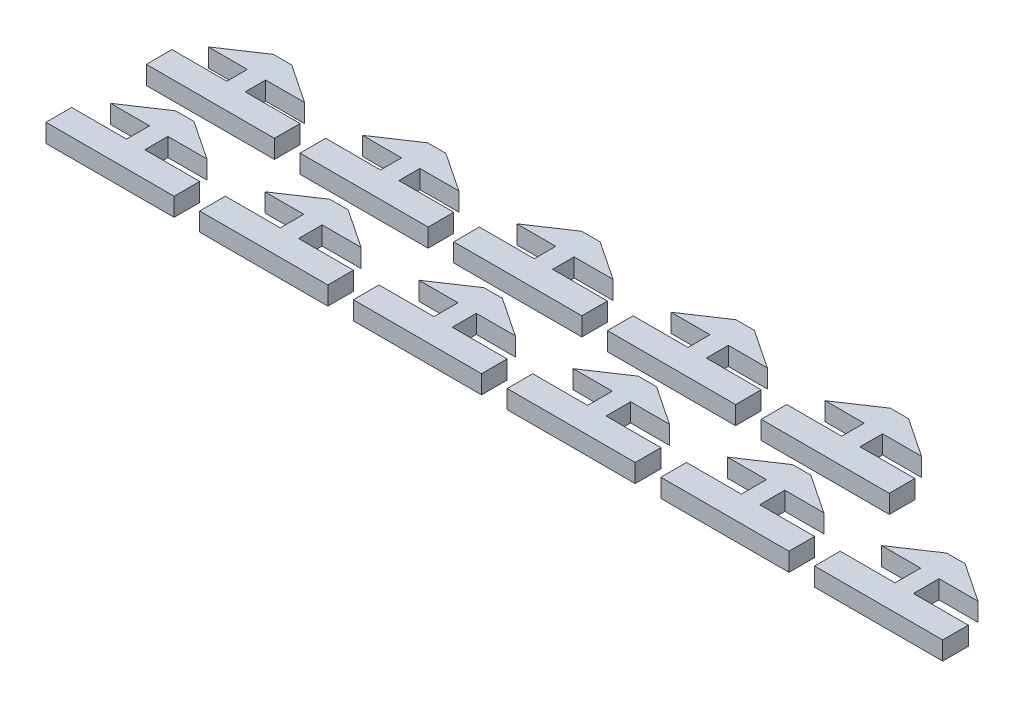
SolidWorks part; units mm, degrees
ref_plane "Front" through (0, 0, 0) normal (0, 0, 1) x (1, 0, 0)
ref_plane "Top" through (0, 0, 0) normal (0, 1, 0) x (1, 0, 0)
ref_plane "Right" through (0, 0, 0) normal (1, 0, 0) x (0, 0, -1)
sketch "Sketch1" plane through (0, 0, 0) normal (0, 1, 0) x (1, 0, 0)
  line L0 (-1.7907, 2) -> (-9.398, 2)
  line L2 (-1.7907, -2) -> (-1.7907, 2)
  line L4 (1.7907, -2) -> (1.7907, 2)
  line L7 (-9.398, 2) -> (-1.7907, 7.08)
  line L8 (-1.7907, 7.08) -> (1.7907, 7.08)
  line L9 (1.7907, 7.08) -> (9.398, 2)
  line L10 (9.398, 2) -> (1.7907, 2)
  line L11 (1.7907, -2) -> (12.5, -2)
  line L12 (-1.7907, -2) -> (-12.5, -2)
  line L13 (-12.5, -2) -> (-12.5, -7)
  line L14 (-12.5, -7) -> (12.5, -7)
  line L15 (12.5, -7) -> (12.5, -2)
  line L16 (12.5, -2) -> (1.7907, -2)
  point P0 (0, 0)
  point P6 (0, -7)
  point P17 (0, 7.08)
  point P24 (1.7907, 0)
  dimension "D1" = 18.796
  dimension "D2" = 3.5814
  dimension "D3" = 25
  dimension "D4" = 5
  dimension "D5" = 5.08
  dimension "D7" = 4
extrude "Boss-Extrude1" add sketch "Sketch1" along normal blind 3.5814 contours L14 L15 L11 L4 L10 L9 L8 L7 L0 L2 L12 L13
sketch "Sketch2" plane through (0, 0, 0) normal (0, 1, 0) x (1, 0, 0)
  line L0 (28.2093, 2.1) -> (20.602, 2.1)
  line L1 (28.2093, -2) -> (28.2093, 2.1)
  line L2 (31.7907, -2) -> (31.7907, 2.1)
  line L3 (20.602, 2.1) -> (28.2093, 7.18)
  line L4 (28.2093, 7.18) -> (31.7907, 7.18)
  line L5 (31.7907, 7.18) -> (39.398, 2.1)
  line L6 (39.398, 2.1) -> (31.7907, 2.1)
  line L7 (-12.5, -2) -> (-12.5, -7) construction
  line L8 (31.7907, -2) -> (42.5, -2)
  line L9 (42.5, -2) -> (42.5, -7)
  line L10 (42.5, -7) -> (17.5, -7)
  line L11 (17.5, -7) -> (17.5, -2)
  line L12 (17.5, -2) -> (28.2093, -2)
  line L13 (-12.5, -7) -> (12.5, -7) construction
  line L14 (12.5, -7) -> (12.5, -2) construction
  line L15 (58.2093, 2.2) -> (50.602, 2.2)
  line L16 (58.2093, -2) -> (58.2093, 2.2)
  line L17 (61.7907, -2) -> (61.7907, 2.2)
  line L18 (50.602, 2.2) -> (58.2093, 7.28)
  line L19 (58.2093, 7.28) -> (61.7907, 7.28)
  line L20 (61.7907, 7.28) -> (69.398, 2.2)
  line L21 (69.398, 2.2) -> (61.7907, 2.2)
  line L22 (61.7907, -2) -> (72.5, -2)
  line L23 (58.2093, -2) -> (47.5, -2)
  line L24 (47.5, -2) -> (47.5, -7)
  line L25 (47.5, -7) -> (72.5, -7)
  line L26 (72.5, -7) -> (72.5, -2)
  line L27 (72.5, -2) -> (61.7907, -2)
  line L28 (88.2093, 2.3) -> (80.602, 2.3)
  line L29 (88.2093, -2) -> (88.2093, 2.3)
  line L30 (91.7907, -2) -> (91.7907, 2.3)
  line L31 (80.602, 2.3) -> (88.2093, 7.38)
  line L32 (88.2093, 7.38) -> (91.7907, 7.38)
  line L33 (91.7907, 7.38) -> (99.398, 2.3)
  line L34 (99.398, 2.3) -> (91.7907, 2.3)
  line L35 (91.7907, -2) -> (102.5, -2)
  line L36 (88.2093, -2) -> (77.5, -2)
  line L37 (77.5, -2) -> (77.5, -7)
  line L38 (77.5, -7) -> (102.5, -7)
  line L39 (102.5, -7) -> (102.5, -2)
  line L40 (102.5, -2) -> (91.7907, -2)
  line L41 (118.2093, 2.4) -> (110.602, 2.4)
  line L42 (118.2093, -2) -> (118.2093, 2.4)
  line L43 (121.7907, -2) -> (121.7907, 2.4)
  line L44 (110.602, 2.4) -> (118.2093, 7.48)
  line L45 (118.2093, 7.48) -> (121.7907, 7.48)
  line L46 (121.7907, 7.48) -> (129.398, 2.4)
  line L47 (129.398, 2.4) -> (121.7907, 2.4)
  line L48 (121.7907, -2) -> (132.5, -2)
  line L49 (118.2093, -2) -> (107.5, -2)
  line L50 (107.5, -2) -> (107.5, -7)
  line L51 (107.5, -7) -> (132.5, -7)
  line L52 (132.5, -7) -> (132.5, -2)
  line L53 (132.5, -2) -> (121.7907, -2)
  line L54 (-1.7907, -17.08) -> (-9.398, -17.08)
  line L55 (-1.7907, -21.58) -> (-1.7907, -17.08)
  line L56 (1.7907, -21.58) -> (1.7907, -17.08)
  line L57 (-9.398, -17.08) -> (-1.7907, -12)
  line L58 (-1.7907, -12) -> (1.7907, -12)
  line L59 (1.7907, -12) -> (9.398, -17.08)
  line L60 (9.398, -17.08) -> (1.7907, -17.08)
  line L61 (1.7907, -21.58) -> (12.5, -21.58)
  line L62 (-1.7907, -21.58) -> (-12.5, -21.58)
  line L63 (-12.5, -21.58) -> (-12.5, -26.58)
  line L64 (-12.5, -26.58) -> (12.5, -26.58)
  line L65 (12.5, -26.58) -> (12.5, -21.58)
  line L66 (12.5, -21.58) -> (1.7907, -21.58)
  line L67 (28.2093, -16.98) -> (20.602, -16.98)
  line L68 (28.2093, -21.58) -> (28.2093, -16.98)
  line L69 (31.7907, -21.58) -> (31.7907, -16.98)
  line L70 (20.602, -16.98) -> (28.2093, -11.9)
  line L71 (28.2093, -11.9) -> (31.7907, -11.9)
  line L72 (31.7907, -11.9) -> (39.398, -16.98)
  line L73 (39.398, -16.98) -> (31.7907, -16.98)
  line L74 (31.7907, -21.58) -> (17.5, -21.58)
  line L75 (28.2093, -21.58) -> (42.5, -21.58)
  line L76 (42.5, -21.58) -> (42.5, -26.58)
  line L77 (42.5, -26.58) -> (17.5, -26.58)
  line L78 (17.5, -26.58) -> (17.5, -21.58)
  line L79 (17.5, -21.58) -> (31.7907, -21.58)
  line L80 (58.2093, -16.88) -> (50.602, -16.88)
  line L81 (58.2093, -21.58) -> (58.2093, -16.88)
  line L82 (61.7907, -21.58) -> (61.7907, -16.88)
  line L83 (50.602, -16.88) -> (58.2093, -11.8)
  line L84 (58.2093, -11.8) -> (61.7907, -11.8)
  line L85 (61.7907, -11.8) -> (69.398, -16.88)
  line L86 (69.398, -16.88) -> (61.7907, -16.88)
  line L87 (61.7907, -21.58) -> (47.5, -21.58)
  line L88 (58.2093, -21.58) -> (72.5, -21.58)
  line L89 (72.5, -21.58) -> (72.5, -26.58)
  line L90 (72.5, -26.58) -> (47.5, -26.58)
  line L91 (47.5, -26.58) -> (47.5, -21.58)
  line L92 (47.5, -21.58) -> (61.7907, -21.58)
  line L93 (88.2093, -16.78) -> (80.602, -16.78)
  line L94 (88.2093, -21.58) -> (88.2093, -16.78)
  line L95 (91.7907, -21.58) -> (91.7907, -16.78)
  line L96 (80.602, -16.78) -> (88.2093, -11.7)
  line L97 (88.2093, -11.7) -> (91.7907, -11.7)
  line L98 (91.7907, -11.7) -> (99.398, -16.78)
  line L99 (99.398, -16.78) -> (91.7907, -16.78)
  line L100 (91.7907, -21.58) -> (102.5, -21.58)
  line L101 (88.2093, -21.58) -> (77.5, -21.58)
  line L102 (77.5, -21.58) -> (77.5, -26.58)
  line L103 (77.5, -26.58) -> (102.5, -26.58)
  line L104 (102.5, -26.58) -> (102.5, -21.58)
  line L105 (102.5, -21.58) -> (91.7907, -21.58)
  line L106 (118.2093, -16.68) -> (110.602, -16.68)
  line L107 (118.2093, -21.58) -> (118.2093, -16.68)
  line L108 (121.7907, -21.58) -> (121.7907, -16.68)
  line L109 (110.602, -16.68) -> (118.2093, -11.6)
  line L110 (118.2093, -11.6) -> (121.7907, -11.6)
  line L111 (121.7907, -11.6) -> (129.398, -16.68)
  line L112 (129.398, -16.68) -> (121.7907, -16.68)
  line L113 (121.7907, -21.58) -> (132.5, -21.58)
  line L114 (118.2093, -21.58) -> (107.5, -21.58)
  line L115 (107.5, -21.58) -> (107.5, -26.58)
  line L116 (107.5, -26.58) -> (132.5, -26.58)
  line L117 (132.5, -26.58) -> (132.5, -21.58)
  line L118 (132.5, -21.58) -> (121.7907, -21.58)
  line L119 (148.2093, -16.58) -> (140.602, -16.58)
  line L120 (148.2093, -21.58) -> (148.2093, -16.58)
  line L121 (151.7907, -21.58) -> (151.7907, -16.58)
  line L122 (140.602, -16.58) -> (148.2093, -11.5)
  line L123 (148.2093, -11.5) -> (151.7907, -11.5)
  line L124 (151.7907, -11.5) -> (159.398, -16.58)
  line L125 (159.398, -16.58) -> (151.7907, -16.58)
  line L126 (151.7907, -21.58) -> (162.5, -21.58)
  line L127 (148.2093, -21.58) -> (137.5, -21.58)
  line L128 (137.5, -21.58) -> (137.5, -26.58)
  line L129 (137.5, -26.58) -> (162.5, -26.58)
  line L130 (162.5, -26.58) -> (162.5, -21.58)
  line L131 (162.5, -21.58) -> (151.7907, -21.58)
  point P0 (30, 0.05)
  point P5 (30, -7)
  point P14 (30, 7.18)
  point P15 (31.7907, 0.05)
  point P20 (60, 0.1)
  point P25 (60, -7)
  point P34 (60, 7.28)
  point P35 (61.7907, 0.1)
  point P36 (90, 0.15)
  point P41 (90, -7)
  point P50 (90, 7.38)
  point P51 (91.7907, 0.15)
  point P52 (120, 0.2)
  point P57 (120, -7)
  point P66 (120, 7.48)
  point P67 (121.7907, 0.2)
  point P68 (0, -19.33)
  point P73 (0, -26.58)
  point P82 (0, -12)
  point P83 (1.7907, -19.33)
  point P84 (30, -19.28)
  point P89 (30, -26.58)
  point P98 (30, -11.9)
  point P99 (31.7907, -19.28)
  point P100 (60, -19.23)
  point P105 (60, -26.58)
  point P114 (60, -11.8)
  point P115 (61.7907, -19.23)
  point P116 (90, -19.18)
  point P121 (90, -26.58)
  point P130 (90, -11.7)
  point P131 (91.7907, -19.18)
  point P132 (120, -19.13)
  point P137 (120, -26.58)
  point P146 (120, -11.6)
  point P147 (121.7907, -19.13)
  point P148 (150, -19.08)
  point P153 (150, -26.58)
  point P162 (150, -11.5)
  point P163 (151.7907, -19.08)
  point P164 (167.5, -41.1953)
  point P165 (88.8846, -31.8567)
  point P166 (-13.8976, -28.4995)
  dimension "D1" = 3.5814
  dimension "D2" = 5
  dimension "D3" = 4.1
  dimension "D4" = 18.796
  dimension "D5" = 5.08
  dimension "D6" = 25
  dimension "D7" = 5
  dimension "D8" = 3.5814
  dimension "D9" = 5
  dimension "D10" = 4.2
  dimension "D11" = 18.796
  dimension "D12" = 5.08
  dimension "D13" = 25
  dimension "D14" = 3.5814
  dimension "D15" = 5
  dimension "D16" = 4.3
  dimension "D17" = 18.796
  dimension "D18" = 5.08
  dimension "D19" = 25
  dimension "D20" = 3.5814
  dimension "D21" = 5
  dimension "D22" = 4.4
  dimension "D23" = 18.796
  dimension "D24" = 5.08
  dimension "D25" = 25
  dimension "D26" = 3.5814
  dimension "D27" = 5
  dimension "D28" = 4.5
  dimension "D29" = 18.796
  dimension "D30" = 5.08
  dimension "D31" = 25
  dimension "D32" = 3.5814
  dimension "D33" = 5
  dimension "D34" = 4.6
  dimension "D35" = 18.796
  dimension "D36" = 5.08
  dimension "D37" = 25
  dimension "D38" = 3.5814
  dimension "D39" = 5
  dimension "D40" = 4.7
  dimension "D41" = 18.796
  dimension "D42" = 5.08
  dimension "D43" = 25
  dimension "D44" = 3.5814
  dimension "D45" = 5
  dimension "D46" = 4.8
  dimension "D47" = 18.796
  dimension "D48" = 5.08
  dimension "D49" = 25
  dimension "D50" = 3.5814
  dimension "D51" = 5
  dimension "D52" = 4.9
  dimension "D53" = 18.796
  dimension "D54" = 5.08
  dimension "D55" = 25
  dimension "D56" = 3.5814
  dimension "D57" = 5
  dimension "D58" = 5
  dimension "D59" = 18.796
  dimension "D60" = 5.08
  dimension "D61" = 25
  dimension "D62" = 5
  dimension "D63" = 5
  dimension "D64" = 5
  dimension "D65" = 5
  dimension "D66" = 5
  dimension "D67" = 5
  dimension "D68" = 5
  dimension "D69" = 5
  dimension "D70" = 5
extrude "Boss-Extrude2" add sketch "Sketch2" along normal up to surface (3.5814 mm away) separate body contours L12 L11 L10 L9 L8 L2 L6 L5 L4 L3 L0 L1 | L25 L26 L22 L17 L21 L20 L19 L18 L15 L16 L23 L24 | L38 L39 L35 L30 L34 L33 L32 L31 L28 L29 L36 L37 | L51 L52 L48 L43 L47 L46 L45 L44 L41 L42 L49 L50 | L64 L65 L61 L56 L60 L59 L58 L57 L54 L55 L62 L63 | L78 L77 L76 L75 L74 | L91 L90 L89 L88 L87 | L74 L69 L73 L72 L71 L70 L67 L68 | L87 L82 L86 L85 L84 L83 L80 L81 | L103 L104 L100 L95 L99 L98 L97 L96 L93 L94 L101 L102 | L116 L117 L113 L108 L112 L111 L110 L109 L106 L107 L114 L115 | L129 L130 L126 L121 L125 L124 L123 L122 L119 L120 L127 L128 up to face at (0, 3.5814, -0.0133)
